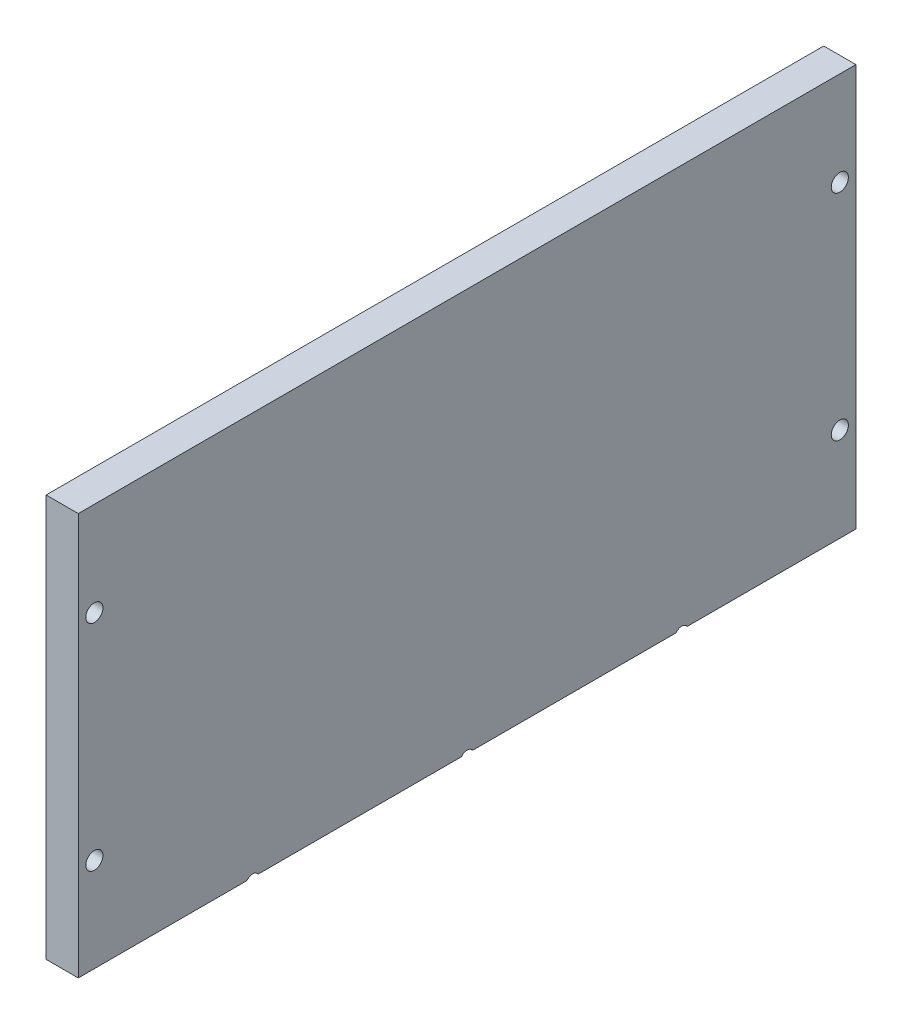
SolidWorks part; units mm, degrees
material "Polypropylene"
ref_plane "正面" through (0, 0, 0) normal (0, 0, 1) x (1, 0, 0)
ref_plane "平面" through (0, 0, 0) normal (0, 1, 0) x (1, 0, 0)
ref_plane "右側面" through (0, 0, 0) normal (1, 0, 0) x (0, 0, -1)
sketch "ｽｹｯﾁ1" plane through (0, 0, 0) normal (0, 1, 0) x (1, 0, 0)
  line L1 (-150, 72.5) -> (150, 72.5)
  line L2 (-150, 72.5) -> (-150, -72.5)
  line L3 (-150, -72.5) -> (150, -72.5)
  line L4 (150, 72.5) -> (150, -72.5)
  line L5 (-150, 72.5) -> (150, -72.5) construction
  line L6 (-150, -72.5) -> (150, 72.5) construction
  point P0 (0, 0)
  dimension "D1" = 300
  dimension "D2" = 145
extrude "ﾎﾞｽ - 押し出し1" add sketch "ｽｹｯﾁ1" along normal blind 81
shell "ｼｪﾙ1" thickness 6
sketch "ｽｹｯﾁ2" plane through (0, 6, 0) normal (0, 1, 0) x (1, 0, 0)
  line L0 (140, 72.5) -> (140, -72.5) construction
  line L1 (150, 72.5) -> (-150, 72.5) construction
  line L2 (-150, -72.5) -> (150, -72.5) construction
  line L3 (140, -72.5) -> (-22.5, -72.5) construction
  line L4 (-22.5, -72.5) -> (-22.5, 72.5) construction
  line L6 (150, -72.5) -> (150, 72.5) construction
  line L7 (-22.5, 0) -> (140, 0) construction
  line L8 (58.75, 72.5) -> (58.75, -72.5) construction
  circle A0 centre (140, 60) radius 2.55
  circle A1 centre (140, -60) radius 2.55
  circle A2 centre (-22.5, -60) radius 2.55
  circle A3 centre (-22.5, 60) radius 2.55
  point P18 (58.75, 0)
  dimension "D3" = 5.1
  dimension "D1" = 162.5
  dimension "D2" = 10
  dimension "D4" = 60
extrude "ｶｯﾄ - 押し出し1" cut sketch "ｽｹｯﾁ2" against normal through all
sketch "ｽｹｯﾁ3" plane through (0, 6, 0) normal (0, 1, 0) x (1, 0, 0)
  circle A0 centre (140, 60) radius 4.25
  circle A1 centre (-22.5, 60) radius 4.25
  circle A2 centre (-22.5, -60) radius 4.25
  circle A3 centre (140, -60) radius 4.25
  dimension "D1" = 8.5
extrude "ｶｯﾄ - 押し出し2" cut sketch "ｽｹｯﾁ3" against normal blind 3
sketch "ｽｹｯﾁ4" plane through (144, 0, 0) normal (-1, 0, 0) x (0, 0, 1)
  line L4 (-72.5, 0) -> (72.5, 0)
  line L5 (72.5, 0) -> (72.5, 81)
  line L6 (72.5, 81) -> (-72.5, 81)
  line L7 (-72.5, 81) -> (-72.5, 0)
  line L8 (-72.5, 0) -> (72.5, 0)
  line L9 (72.5, 0) -> (72.5, 81)
  line L10 (72.5, 81) -> (-72.5, 81)
  line L11 (-72.5, 81) -> (-72.5, 0)
  dimension "D1" = 0
extrude "ｶｯﾄ - 押し出し3" cut sketch "ｽｹｯﾁ4" along normal through all contours L11 L8 L9 L10
sketch "ｽｹｯﾁ5" plane through (144, 0, 0) normal (-1, 0, 0) x (0, 0, 1)
  line L0 (72.5, 0) -> (72.5, 81) construction
  line L1 (-72.5, 0) -> (72.5, 0)
  line L2 (-72.5, 0) -> (-72.5, 6)
  line L3 (-72.5, 6) -> (72.5, 6)
  line L4 (72.5, 0) -> (72.5, 6)
  dimension "D1" = 6
extrude "ｶｯﾄ - 押し出し4" cut sketch "ｽｹｯﾁ5" against normal through all
sketch "ｽｹｯﾁ6" plane through (144, 0, 0) normal (-1, 0, 0) x (0, 0, 1)
  line L0 (-69.5, 81) -> (-69.5, 6) construction
  line L1 (72.5, 81) -> (-72.5, 81) construction
  line L2 (72.5, 6) -> (-72.5, 6) construction
  line L3 (-72.5, 81) -> (-72.5, 6) construction
  line L4 (0, 81) -> (0, 6) construction
  line L5 (-72.5, 43.5) -> (72.5, 43.5) construction
  line L6 (72.5, 6) -> (72.5, 81) construction
  circle A0 centre (-69.5, 63.5) radius 1.6
  circle A2 centre (-69.5, 23.5) radius 1.6
  circle A3 centre (69.5, 23.5) radius 1.6
  circle A4 centre (69.5, 63.5) radius 1.6
  circle A5 centre (-40, 5.3) radius 1.25
  circle A6 centre (0, 5.3) radius 1.25
  circle A7 centre (40, 5.3) radius 1.25
  point P24 (-1.7854, 5.3)
  dimension "D2" = 40
  dimension "D3" = 3.2
  dimension "D4" = 2.5
  dimension "D7" = 0.7
  dimension "D1" = 3
  dimension "D5" = 40
  dimension "D6" = 0.7
extrude "ｶｯﾄ - 押し出し5" cut sketch "ｽｹｯﾁ6" against normal through all
sketch "ｽｹｯﾁ7" plane through (144, 0, 0) normal (-1, 0, 0) x (0, 0, 1)
  circle A0 centre (-69.5, 63.5) radius 2.95
  circle A1 centre (-69.5, 23.5) radius 2.95
  circle A2 centre (69.5, 63.5) radius 2.95
  circle A3 centre (69.5, 23.5) radius 2.95
  dimension "D1" = 5.9
extrude "ｶｯﾄ - 押し出し6" cut sketch "ｽｹｯﾁ7" against normal blind 3
sketch "ｽｹｯﾁ8" plane through (0, 6, 0) normal (0, -1, 0) x (1, 0, 0)
  line L0 (147, 72.45) -> (147, -72.5) construction
  line L1 (150, -72.5) -> (144, -72.5) construction
  line L2 (144, 40) -> (150, 40) construction
  line L3 (144, 41.0356) -> (144, 38.9644) construction
  line L4 (150, 38.9644) -> (150, 41.0356) construction
  line L5 (144, 0) -> (150, 0) construction
  line L6 (144, 1.0356) -> (144, -1.0356) construction
  line L7 (150, -1.0356) -> (150, 1.0356) construction
  line L8 (144, -40) -> (150, -40) construction
  line L9 (144, -38.9644) -> (144, -41.0356) construction
  line L10 (150, -41.0356) -> (150, -38.9644) construction
  circle A0 centre (147, 40) radius 1.5
  circle A1 centre (147, -0.025) radius 1.5
  circle A2 centre (147, -40) radius 1.5
  dimension "D1" = 3
extrude "ｶｯﾄ - 押し出し7" cut sketch "ｽｹｯﾁ8" against normal blind 10
